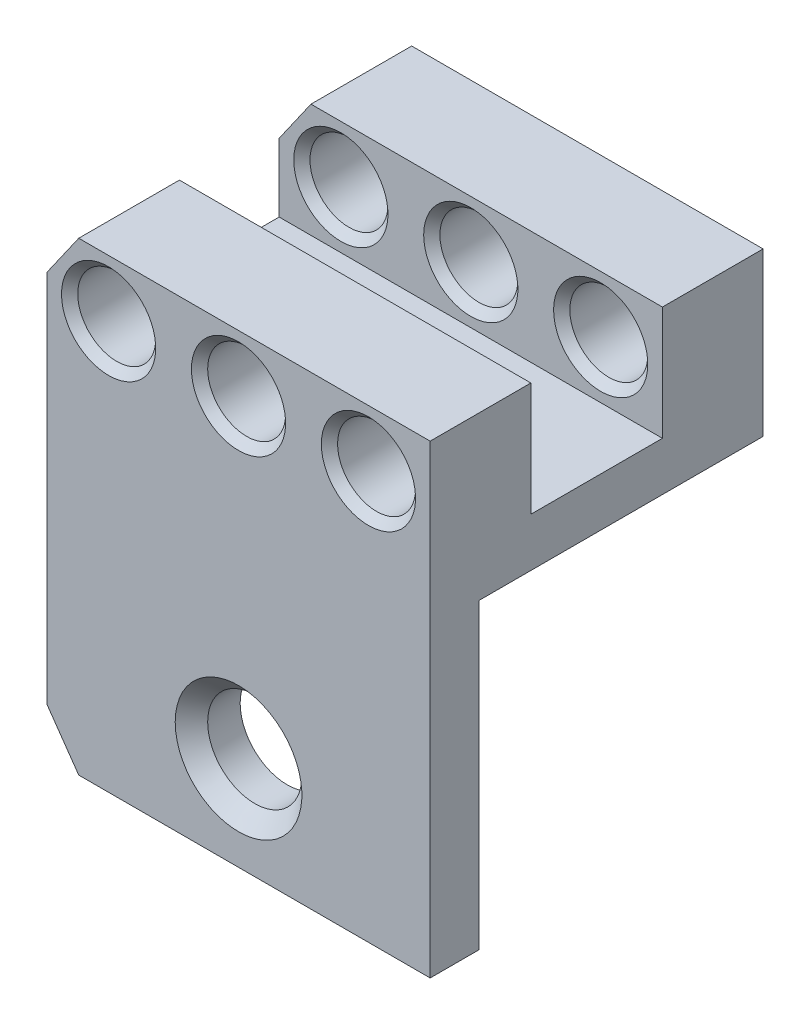
SolidWorks part; units mm, degrees
ref_plane "Front Plane" through (0, 0, 0) normal (0, 0, 1) x (1, 0, 0)
ref_plane "Top Plane" through (0, 0, 0) normal (0, 1, 0) x (1, 0, 0)
ref_plane "Right Plane" through (0, 0, 0) normal (1, 0, 0) x (0, 0, -1)
sketch "Sketch1" plane through (0, 0, 0) normal (0, 0, 1) x (1, 0, 0)
  line L6 (0, 0) -> (-23.6, 0)
  line L7 (-23.6, 0) -> (-23.6, -14.4)
  line L9 (-19.3, -18.6288) -> (-4.3, -18.6288)
  line L11 (0, -14.2564) -> (0, 0)
  line L12 (0, -14.2564) -> (0, -18.6288)
  line L13 (0, -18.6288) -> (-4.3, -18.6288)
  line L14 (-23.6, -14.4) -> (-23.6, -18.6288)
  line L15 (-23.6, -18.6288) -> (-19.3, -18.6288)
  circle A0 centre (-11.8, -12.8288) radius 2.9
  point P6 (-11.8, 0)
  point P7 (-11.8, -18.6288)
  dimension "D5" = 5.8
  dimension "D1" = 23.6
  dimension "D2" = 14.4
  dimension "D3" = 15
  dimension "D4" = 6.1325
  dimension "D6" = 5.8
  dimension "D7" = 6.031
extrude "Boss-Extrude1" add sketch "Sketch1" along normal blind 3
sketch "Sketch2" plane through (0, 0, 0) normal (0, 1, 0) x (1, 0, 0)
  line L0 (-23.6, -3) -> (-23.6, 17.5)
  line L1 (-23.6, 17.5) -> (0, 17.5)
  line L2 (0, 17.5) -> (0, -3)
  line L3 (0, -3) -> (-23.6, -3)
  dimension "D1" = 20.5
extrude "Boss-Extrude2" add sketch "Sketch2" along normal blind 3
sketch "Sketch3" plane through (0, 3, 0) normal (0, 1, 0) x (1, 0, 0)
  line L0 (-23.6, -3) -> (-23.6, 3.2)
  line L1 (-23.6, 17.5) -> (-23.6, -3) construction
  line L2 (-23.6, 3.2) -> (0, 3.2)
  line L3 (0, -3) -> (0, 17.5) construction
  line L4 (0, 3.2) -> (0, -3)
  line L5 (0, -3) -> (-23.6, -3)
  line L6 (-23.6, 17.5) -> (0, 17.5)
  line L7 (0, 17.5) -> (0, 11.3)
  line L8 (0, 11.3) -> (-23.6, 11.3)
  line L9 (-23.6, 11.3) -> (-23.6, 17.5)
  dimension "D1" = 6.2
  dimension "D2" = 6.2
extrude "Boss-Extrude3" add sketch "Sketch3" along normal blind 7
sketch "Sketch4" plane through (0, 0, 3) normal (0, 0, 1) x (1, 0, 0)
  line L0 (-23.6, 10) -> (0, 10) construction
  line L2 (-11.8, 10) -> (-11.8, -3.0183) construction
  circle A0 centre (-11.8, 6.5) radius 2.4
  circle A1 centre (-19.8, 6.5) radius 2.4
  circle A2 centre (-3.8, 6.5) radius 2.4
  dimension "D1" = 4.8
  dimension "D2" = 4.8
  dimension "D3" = 4.8
  dimension "D4" = 8
  dimension "D5" = 8
  dimension "D6" = 3.5
extrude "Cut-Extrude2" cut sketch "Sketch4" against normal through all
chamfer "Chamfer1" distance 2.8 angle 35 3 edges at (-23.6, 10, -14.4) (-23.6, 10, -0.1) (-23.6, -18.6288, 1.5)
chamfer "Chamfer2" distance 1 angle 45 1 edges at (-8.9, -12.8288, 3)
chamfer "Chamfer3" distance 0.5 angle 45 12 edges at (-17.4, 6.5, -17.5) (-9.4, 6.5, -17.5) (-1.4, 6.5, -17.5) (-17.4, 6.5, 3) (-17.4, 6.5, -3.2) (-22.2, 6.5, -11.3) (-9.4, 6.5, 3) (-9.4, 6.5, -3.2) (-14.2, 6.5, -11.3) (-1.4, 6.5, 3) (-1.4, 6.5, -3.2) (-6.2, 6.5, -11.3)
